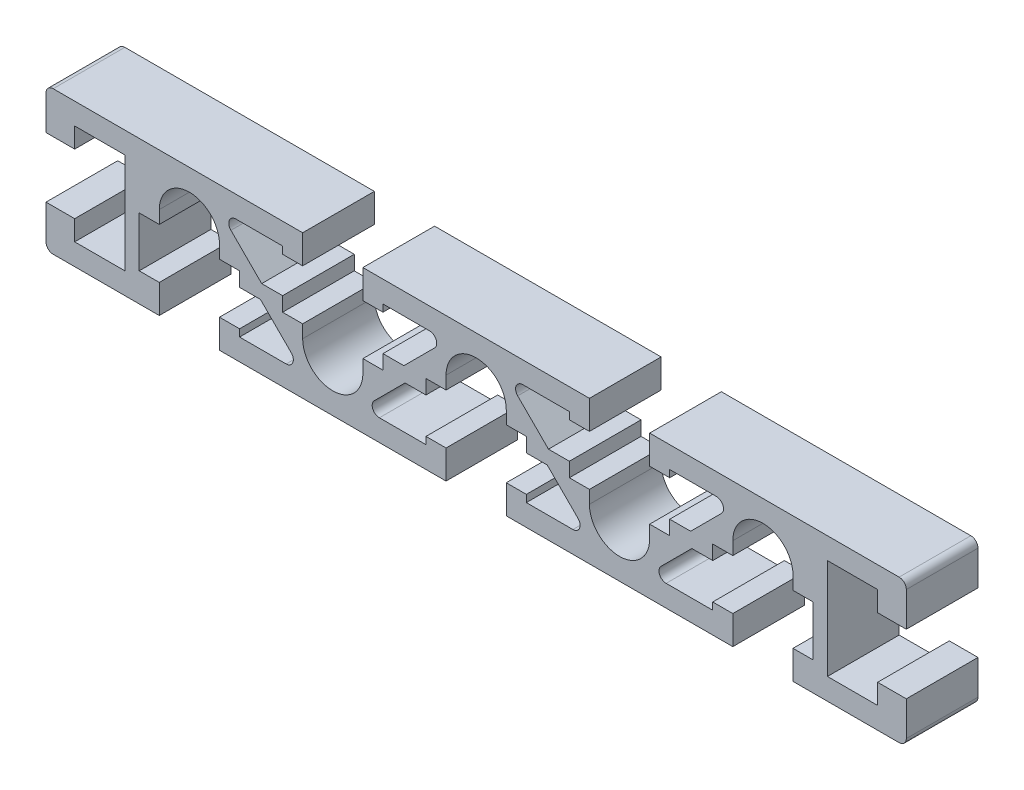
SolidWorks part; units mm, degrees
ref_plane "前视基准面" through (0, 0, 0) normal (0, 0, 1) x (1, 0, 0)
ref_plane "上视基准面" through (0, 0, 0) normal (0, 1, 0) x (1, 0, 0)
ref_plane "右视基准面" through (0, 0, 0) normal (1, 0, 0) x (0, 0, -1)
sketch "草图1" plane through (0, 0, 0) normal (0, 0, 1) x (1, 0, 0)
  line B0 (66.5313, 17) -> (73.0313, 17)
  line B1 (73.0313, 17) -> (73.0313, 16)
  line B2 (73.0313, 16) -> (75.8313, 16)
  line B3 (75.8313, 16) -> (75.8313, 20)
  line B4 (75.8313, 20) -> (60.0313, 20)
  line B5 (60.0313, 20) -> (44.2313, 20)
  line B6 (44.2313, 20) -> (44.2313, 16)
  line B7 (44.2313, 16) -> (47.0313, 16)
  line B8 (47.0313, 16) -> (47.0313, 17)
  line B9 (47.0313, 17) -> (53.5313, 17)
  line B10 (54.2384, 15.2929) -> (49.9455, 11)
  line B11 (49.9455, 11) -> (47.0313, 11)
  line B12 (47.0313, 11) -> (47.0313, 9)
  line B13 (47.0313, 9) -> (44.2313, 9)
  line B14 (44.2313, 9) -> (44.2313, 7.2)
  line B15 (35.8313, 7.2) -> (35.8313, 9)
  line B16 (35.8313, 9) -> (33.0313, 9)
  line B17 (33.0313, 9) -> (33.0313, 11)
  line B18 (33.0313, 11) -> (30.117, 11)
  line B19 (30.117, 11) -> (25.8241, 15.2929)
  line B20 (26.5313, 17) -> (33.0313, 17)
  line B21 (33.0313, 17) -> (33.0313, 16)
  line B22 (33.0313, 16) -> (35.8313, 16)
  line B23 (35.8313, 16) -> (35.8313, 20)
  line B24 (35.8313, 20) -> (1.0313, 20)
  line B25 (0.0313, 19) -> (0.0313, 14.2)
  line B26 (0.0313, 14.2) -> (4.0313, 14.2)
  line B27 (4.0313, 14.2) -> (4.0313, 17)
  line B28 (4.0313, 17) -> (11.0313, 17)
  line B29 (11.0313, 17) -> (11.0313, 3)
  line B30 (11.0313, 3) -> (4.0313, 3)
  line B31 (4.0313, 3) -> (4.0313, 5.8)
  line B32 (4.0313, 5.8) -> (0.0313, 5.8)
  line B33 (0.0313, 5.8) -> (0.0313, 1)
  line B34 (1.0313, 0) -> (15.8313, 0)
  line B35 (15.8313, 0) -> (15.8313, 4)
  line B36 (15.8313, 4) -> (13.0313, 4)
  line B37 (13.0313, 4) -> (13.0313, 11)
  line B38 (13.0313, 11) -> (15.8313, 11)
  line B39 (15.8313, 11) -> (15.8313, 12.8)
  line B40 (24.2313, 12.8) -> (24.2313, 11)
  line B41 (24.2313, 11) -> (27.0313, 11)
  line B42 (27.0313, 11) -> (27.0313, 9)
  line B43 (27.0313, 9) -> (29.9455, 9)
  line B44 (29.9455, 9) -> (34.2384, 4.7071)
  line B45 (33.5313, 3) -> (27.0313, 3)
  line B46 (27.0313, 3) -> (27.0313, 4)
  line B47 (27.0313, 4) -> (24.2313, 4)
  line B48 (24.2313, 4) -> (24.2313, 0)
  line B49 (24.2313, 0) -> (55.8313, 0)
  line B50 (55.8313, 0) -> (55.8313, 4)
  line B51 (55.8313, 4) -> (53.0313, 4)
  line B52 (53.0313, 4) -> (53.0313, 3)
  line B53 (53.0313, 3) -> (46.5313, 3)
  line B54 (45.8241, 4.7071) -> (50.117, 9)
  line B55 (50.117, 9) -> (53.0313, 9)
  line B56 (53.0313, 9) -> (53.0313, 11)
  line B57 (53.0313, 11) -> (55.8313, 11)
  line B58 (55.8313, 11) -> (55.8313, 12.8)
  line B59 (64.2313, 12.8) -> (64.2313, 11)
  line B60 (64.2313, 11) -> (67.0313, 11)
  line B61 (67.0313, 11) -> (67.0313, 9)
  line B62 (67.0313, 9) -> (69.9455, 9)
  line B63 (69.9455, 9) -> (74.2384, 4.7071)
  line B64 (73.5313, 3) -> (67.0313, 3)
  line B65 (67.0313, 3) -> (67.0313, 4)
  line B66 (67.0313, 4) -> (64.2313, 4)
  line B67 (64.2313, 4) -> (64.2313, 0)
  line B68 (64.2313, 0) -> (95.8313, 0)
  line B69 (95.8313, 0) -> (95.8313, 4)
  line B70 (95.8313, 4) -> (93.0313, 4)
  line B71 (93.0313, 4) -> (93.0313, 3)
  line B72 (93.0313, 3) -> (86.5313, 3)
  line B73 (85.8241, 4.7071) -> (90.117, 9)
  line B74 (90.117, 9) -> (93.0313, 9)
  line B75 (93.0313, 9) -> (93.0313, 11)
  line B76 (93.0313, 11) -> (95.8313, 11)
  line B77 (95.8313, 11) -> (95.8313, 12.8)
  line B78 (104.2313, 12.8) -> (104.2313, 11)
  line B79 (104.2313, 11) -> (107.0313, 11)
  line B80 (107.0313, 11) -> (107.0313, 4)
  line B81 (107.0313, 4) -> (104.2313, 4)
  line B82 (104.2313, 4) -> (104.2313, 0)
  line B83 (104.2313, 0) -> (119.0313, 0)
  line B84 (120.0313, 1) -> (120.0313, 5.8)
  line B85 (120.0313, 5.8) -> (116.0313, 5.8)
  line B86 (116.0313, 5.8) -> (116.0313, 3)
  line B87 (116.0313, 3) -> (109.0313, 3)
  line B88 (109.0313, 3) -> (109.0313, 17)
  line B89 (109.0313, 17) -> (116.0313, 17)
  line B90 (116.0313, 17) -> (116.0313, 14.2)
  line B91 (116.0313, 14.2) -> (120.0313, 14.2)
  line B92 (120.0313, 14.2) -> (120.0313, 19)
  line B93 (119.0313, 20) -> (84.2313, 20)
  line B94 (84.2313, 20) -> (84.2313, 16)
  line B95 (84.2313, 16) -> (87.0313, 16)
  line B96 (87.0313, 16) -> (87.0313, 17)
  line B97 (87.0313, 17) -> (93.5313, 17)
  line B98 (94.2384, 15.2929) -> (89.9455, 11)
  line B99 (89.9455, 11) -> (87.0313, 11)
  line B100 (87.0313, 11) -> (87.0313, 9)
  line B101 (87.0313, 9) -> (84.2313, 9)
  line B102 (84.2313, 9) -> (84.2313, 7.2)
  line B103 (75.8313, 7.2) -> (75.8313, 9)
  line B104 (75.8313, 9) -> (73.0313, 9)
  line B105 (73.0313, 9) -> (73.0313, 11)
  line B106 (73.0313, 11) -> (70.117, 11)
  line B107 (70.117, 11) -> (65.8241, 15.2929)
  arc B108 (66.5313, 17) -> (65.8241, 15.2929) centre (66.5313, 16) ccw
  arc B109 (54.2384, 15.2929) -> (53.5313, 17) centre (53.5313, 16) ccw
  arc B110 (35.8313, 7.2) -> (44.2313, 7.2) centre (40.0313, 7.2) ccw
  arc B111 (26.5313, 17) -> (25.8241, 15.2929) centre (26.5313, 16) ccw
  arc B112 (1.0313, 20) -> (0.0313, 19) centre (1.0313, 19) ccw
  arc B113 (0.0313, 1) -> (1.0313, 0) centre (1.0313, 1) ccw
  arc B114 (24.2313, 12.8) -> (15.8313, 12.8) centre (20.0313, 12.8) ccw
  arc B115 (33.5313, 3) -> (34.2384, 4.7071) centre (33.5313, 4) ccw
  arc B116 (45.8241, 4.7071) -> (46.5313, 3) centre (46.5313, 4) ccw
  arc B117 (60.0313, 17) -> (55.8313, 12.8) centre (60.0313, 12.8) ccw
  arc B118 (64.2313, 12.8) -> (60.0313, 17) centre (60.0313, 12.8) ccw
  arc B119 (73.5313, 3) -> (74.2384, 4.7071) centre (73.5313, 4) ccw
  arc B120 (85.8241, 4.7071) -> (86.5313, 3) centre (86.5313, 4) ccw
  arc B121 (104.2313, 12.8) -> (95.8313, 12.8) centre (100.0313, 12.8) ccw
  arc B122 (119.0313, 0) -> (120.0313, 1) centre (119.0313, 1) ccw
  arc B123 (120.0313, 19) -> (119.0313, 20) centre (119.0313, 19) ccw
  arc B124 (94.2384, 15.2929) -> (93.5313, 17) centre (93.5313, 16) ccw
  arc B125 (75.8313, 7.2) -> (84.2313, 7.2) centre (80.0313, 7.2) ccw
sketch_block_instance "A$C38A20983-1"
sketch_block "A$C38A20983"
extrude "凸台-拉伸1" add sketch "草图1" along normal blind 10
